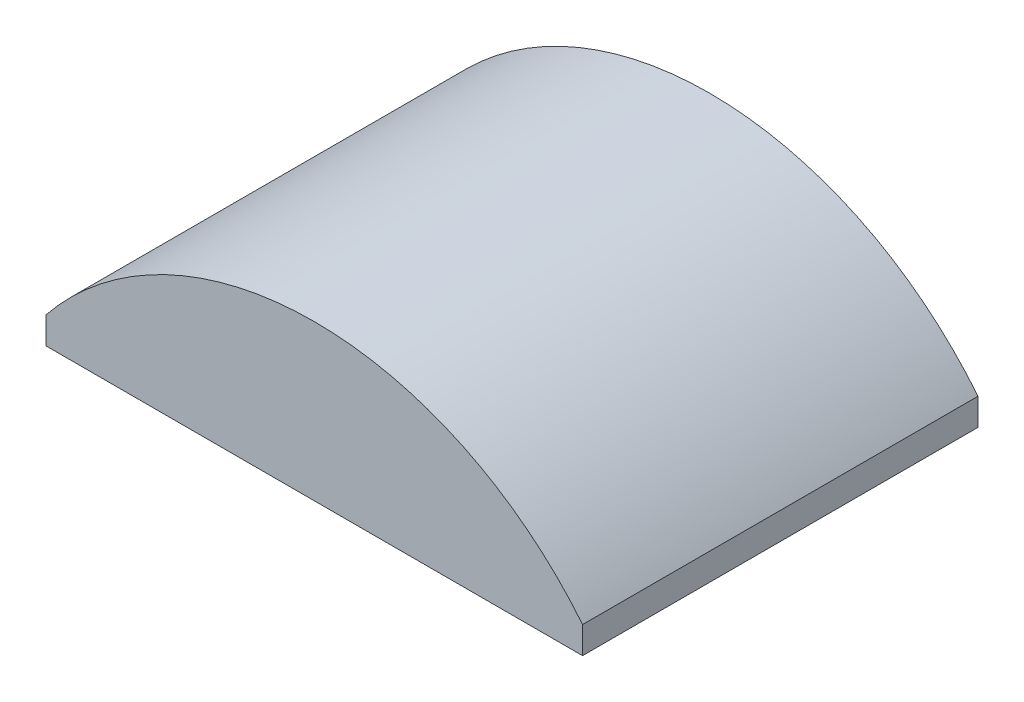
SolidWorks part; units mm, degrees
ref_plane "Front Plane" through (0, 0, 0) normal (0, 0, 1) x (1, 0, 0)
ref_plane "Top Plane" through (0, 0, 0) normal (0, 1, 0) x (1, 0, 0)
ref_plane "Right Plane" through (0, 0, 0) normal (1, 0, 0) x (0, 0, -1)
sketch "Sketch1" plane through (0, 0, 0) normal (0, 0, 1) x (1, 0, 0)
  line L1 (-29.85, 0) -> (29.85, 0)
  line L2 (-29.85, 0) -> (-29.85, 3)
  line L3 (-29.85, 3) -> (29.85, 3)
  line L4 (29.85, 0) -> (29.85, 3)
  circle A0 centre (0, -21.077) radius 38.35
  point P4 (0, 0)
  point P8 (0, 0)
  point P9 (0, -18.6413)
  point P10 (0, 0)
  dimension "D3" = 76.7
  dimension "D1" = 3
  dimension "D2" = 59.7
extrude "Boss-Extrude1" add sketch "Sketch1" along normal blind 44 contours L3 A0 | L1 L4 L3 L2
sketch "Sketch2" plane through (0, 0, 0) normal (0, -1, 0) x (1, 0, 0)
  line L0 (-29.85, 22) -> (29.85, 22) construction
  line L1 (-29.85, 44) -> (-29.85, 0) construction
  line L2 (29.85, 44) -> (29.85, 0) construction
  line L3 (0, 44) -> (0, 0) construction
  line L4 (-29.85, 44) -> (29.85, 44) construction
  line L5 (0, 22) -> (8.8388, 30.8388) construction
  circle A0 centre (0, 22) radius 12.5 construction
  circle A1 centre (8.8388, 30.8388) radius 3.5
  circle A2 centre (8.8388, 30.8388) radius 2.25
  circle A3 centre (8.8388, 13.1612) radius 2.25
  circle A4 centre (8.8388, 13.1612) radius 3.5
  circle A5 centre (-8.8388, 13.1612) radius 2.25
  circle A6 centre (-8.8388, 13.1612) radius 3.5
  circle A7 centre (-8.8388, 30.8388) radius 2.25
  circle A8 centre (-8.8388, 30.8388) radius 3.5
  dimension "D1" = 25
  dimension "D3" = 7
  dimension "D4" = 4.5
  dimension "D2" = 45
  dimension "D5" = 4
extrude "Boss-Extrude2" add sketch "Sketch2" along normal blind 9
sketch "Sketch3" plane through (0, 0, 0) normal (0, -1, 0) x (1, 0, 0)
  circle A0 centre (8.8388, 30.8388) radius 6.2
  circle A1 centre (8.8388, 13.1612) radius 6.2
  circle A2 centre (-8.8388, 13.1612) radius 6.2
  circle A3 centre (-8.8388, 30.8388) radius 6.2
  circle A4 centre (-8.8388, 13.1612) radius 3.5 construction
  circle A5 centre (-8.8388, 30.8388) radius 3.5 construction
  circle A6 centre (8.8388, 30.8388) radius 3.5 construction
  circle A7 centre (-8.8388, 13.1612) radius 3.5
  circle A8 centre (-8.8388, 30.8388) radius 3.5
  circle A9 centre (8.8388, 30.8388) radius 3.5
  circle A10 centre (8.8388, 13.1612) radius 3.5 construction
  circle A11 centre (8.8388, 30.8388) radius 3.5
  circle A12 centre (-8.8388, 30.8388) radius 3.5
  circle A13 centre (-8.8388, 13.1612) radius 3.5
  circle A14 centre (8.8388, 13.1612) radius 3.5
  circle M7 centre (-8.8388, 30.8388) radius 3.5
  circle M8 centre (-8.8388, 13.1612) radius 3.5
  circle M9 centre (8.8388, 13.1612) radius 3.5
  circle M10 centre (8.8388, 30.8388) radius 3.5
  dimension "D1" = 12.4
extrude "Cut-Extrude1" cut sketch "Sketch3" against normal blind 8 contours A3 M7 | A0 M10 | A1 M9 | A2 M8
chamfer "Chamfer1" distance 0.75 angle 45 4 edges at (15.0388, 0, 13.1612) (15.0388, 0, 30.8388) (-2.6388, 0, 30.8388) (-2.6388, 0, 13.1612)
